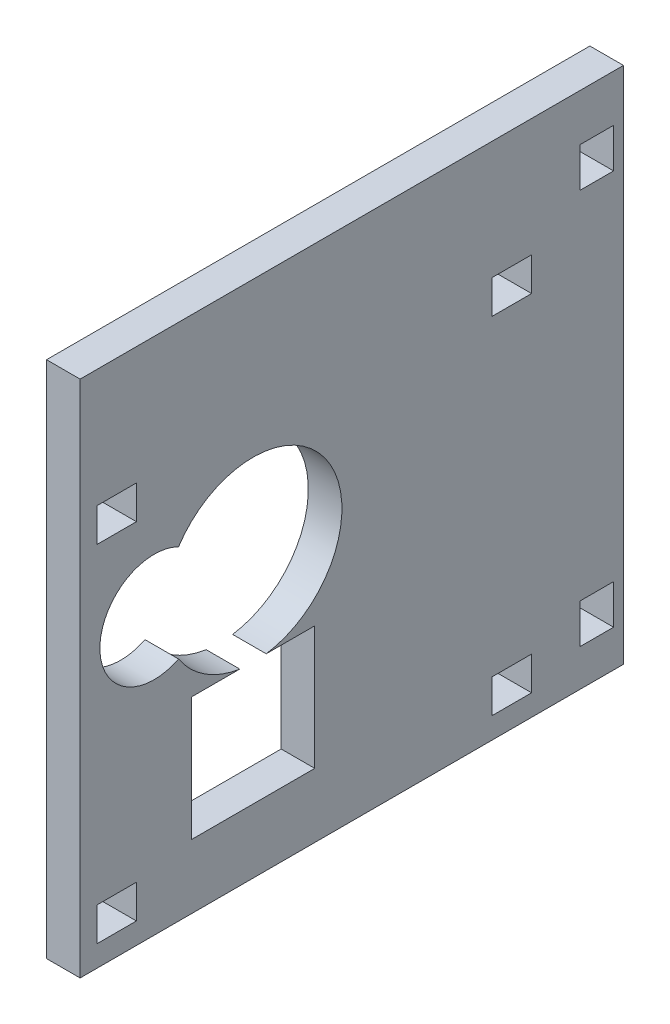
SolidWorks part; units mm, degrees
material "Delrin 2700 NC010, Low Viscosity Acetal Copolymer (SS)"
ref_plane "Front Plane" through (0, 0, 0) normal (0, 0, 1) x (1, 0, 0)
ref_plane "Top Plane" through (0, 0, 0) normal (0, 1, 0) x (1, 0, 0)
ref_plane "Right Plane" through (0, 0, 0) normal (1, 0, 0) x (0, 0, -1)
sketch "Sketch1" plane through (0, 0, 0) normal (1, 0, 0) x (0, 0, -1)
  line L0 (8.89, -989.078) -> (8.89, 49010.922) construction
  line L1 (0, 0) -> (27.94, 0)
  line L2 (0, 0) -> (0, 27.94)
  line L3 (0, 27.94) -> (27.94, 27.94)
  line L4 (27.94, 0) -> (27.94, 27.94)
  line L5 (12.065, 4.572) -> (5.715, 4.572)
  line L6 (12.065, 4.572) -> (12.065, 10.922)
  line L7 (12.065, 10.922) -> (5.715, 10.922)
  line L8 (5.715, 4.572) -> (5.715, 10.922)
  line L9 (0, 13.97) -> (27.94, 13.97) construction
  line L10 (27.432, 5.207) -> (25.7048, 5.207)
  line L11 (27.432, 25.527) -> (25.7048, 25.527)
  line L12 (27.432, 25.527) -> (27.432, 23.495)
  line L13 (27.432, 23.495) -> (25.7048, 23.495)
  line L14 (25.7048, 25.527) -> (25.7048, 23.495)
  line L15 (27.432, 5.207) -> (27.432, 3.175)
  line L16 (27.432, 3.175) -> (25.7048, 3.175)
  line L17 (25.7048, 5.207) -> (25.7048, 3.175)
  line L18 (27.432, 25.527) -> (27.432, 5.207) construction
  point P25 (8.89, 10.922)
  dimension "D1" = 27.94
  dimension "D2" = 27.94
  dimension "D3" = 6.35
  dimension "D4" = 6.35
  dimension "D5" = 15.875
  dimension "D6" = 4.572
  dimension "D8" = 2.032
  dimension "D9" = 1.7272
  dimension "D10" = 0.508
  dimension "D11" = 2
  dimension "D12" = 20.32
extrude "Boss-Extrude1" add sketch "Sketch1" along normal blind 1.7272
sketch "Sketch4" plane through (1.7272, 0, 0) normal (1, 0, 0) x (0, 0, -1)
  line L0 (8.89, -984.4908) -> (8.89, 49015.5092) construction
  line L1 (12.065, 10.922) -> (5.715, 10.922) construction
  line L2 (12.065, 10.922) -> (5.715, 10.922) construction
  line L3 (5.715, 4.572) -> (12.065, 4.572) construction
  circle A0 centre (8.89, 15.4432) radius 4.572
  circle A1 centre (3.81, 15.4432) radius 2.794
  point P10 (8.89, 4.572)
  line M20 (5.715, 10.922) -> (12.065, 10.922)
  dimension "D1" = 9.144
  dimension "D2" = 5.588
  dimension "D3" = 5.08
  dimension "D4" = 4.5212
extrude "Cut-Extrude4" cut sketch "Sketch4" against normal up to surface (1.7272 mm away) contours A1 A0 M20 | A0 A1 | A0 A1 up to face at (0, 24.511, -26.5684)
sketch "Sketch8" plane through (0, 20.1422, 3.5052) normal (1, 0, 0) x (0, -1, 0)
  line L8 (0, 26.7208) -> (0, 24.6888)
  line L9 (0, 24.6888) -> (-1.7272, 24.6888)
  line L10 (-1.7272, 24.6888) -> (-1.7272, 26.7208)
  line L11 (-1.7272, 26.7208) -> (0, 26.7208)
  line L12 (0, 6.4008) -> (0, 4.3688)
  line L13 (0, 4.3688) -> (-1.7272, 4.3688)
  line L14 (-1.7272, 4.3688) -> (-1.7272, 6.4008)
  line L15 (-1.7272, 6.4008) -> (0, 6.4008)
extrude "Cut-Extrude5" cut sketch "Sketch8" along normal up to surface (1.7272 mm away) up to face at (1.7272, 24.511, -26.5684)
sketch "Sketch9" plane through (0, 2.3622, 3.5052) normal (1, 0, 0) x (0, -1, 0)
  line L8 (0, 26.7208) -> (0, 24.6888)
  line L9 (0, 24.6888) -> (-1.7272, 24.6888)
  line L10 (-1.7272, 24.6888) -> (-1.7272, 26.7208)
  line L11 (-1.7272, 26.7208) -> (0, 26.7208)
  line L12 (0, 6.4008) -> (0, 4.3688)
  line L13 (0, 4.3688) -> (-1.7272, 4.3688)
  line L14 (-1.7272, 4.3688) -> (-1.7272, 6.4008)
  line L15 (-1.7272, 6.4008) -> (0, 6.4008)
extrude "Cut-Extrude6" cut sketch "Sketch9" along normal up to surface (1.7272 mm away) up to face at (1.7272, 21.0058, -22.1996)
sketch "Sketch10" plane through (1.7272, 0, 0) normal (1, 0, 0) x (0, 0, -1)
  line L0 (0, 27.94) -> (0, 0) construction
  line L1 (0, 1.27) -> (27.94, 1.27)
  line L2 (0, 1.27) -> (0, 0)
  line L3 (0, 0) -> (27.94, 0)
  line L4 (27.94, 1.27) -> (27.94, 0)
  line L5 (27.94, 0) -> (27.94, 27.94) construction
  line L6 (0, 0) -> (27.94, 0) construction
  dimension "D1" = 1.27
extrude "Cut-Extrude7" cut sketch "Sketch10" against normal up to surface (1.7272 mm away) up to face at (0, 3.2258, -22.1996)
